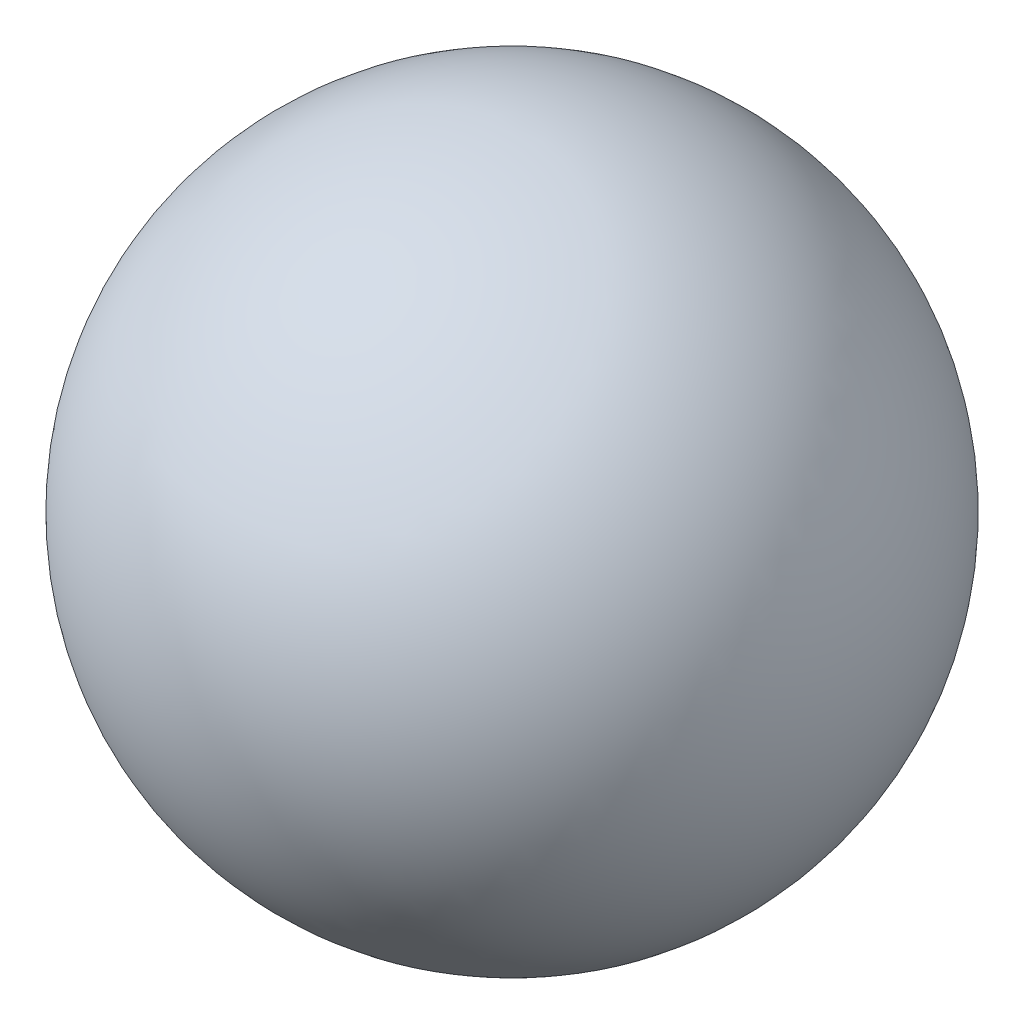
SolidWorks part; units mm, degrees
ref_plane "Front Plane" through (0, 0, 0) normal (0, 0, 1) x (1, 0, 0)
ref_plane "Top Plane" through (0, 0, 0) normal (0, 1, 0) x (1, 0, 0)
ref_plane "Right Plane" through (0, 0, 0) normal (1, 0, 0) x (0, 0, -1)
ref_plane "Plane1" through (0, 0, 0) normal (0, 0, -1) x (-1, 0, 0)
sketch "Sketch1" plane through (0, 0, 0) normal (0, 0, -1) x (-1, 0, 0)
  line L0 (0, 3.21) -> (0, 4.7275)
  line L1 (0, 3.21) -> (0, 4.7275) construction
  arc A0 (0, 4.7275) -> (0, 3.21) centre (0, 3.9688) ccw
revolve "Revolve1" add sketch "Sketch1" angle 360 about L1
